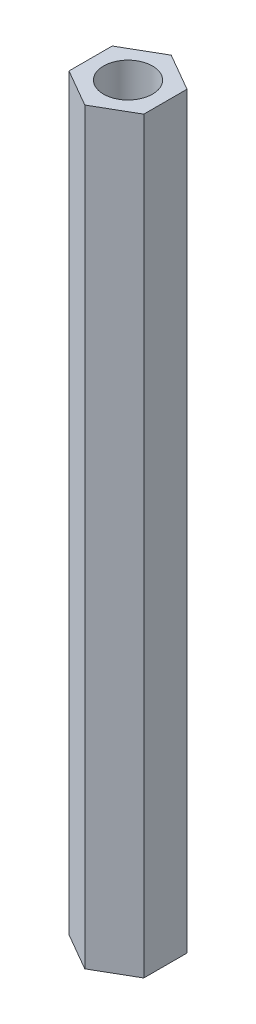
SolidWorks part; units mm, degrees
ref_plane "Front Plane" through (0, 0, 0) normal (0, 0, 1) x (1, 0, 0)
ref_plane "Top Plane" through (0, 0, 0) normal (0, 1, 0) x (1, 0, 0)
ref_plane "Right Plane" through (0, 0, 0) normal (1, 0, 0) x (0, 0, -1)
sketch "Sketch1" plane through (0, 0, 0) normal (0, 1, 0) x (1, 0, 0)
  line L0 (2.5002, 1.4435) -> (2.5002, -1.4435)
  line L1 (2.5002, -1.4435) -> (0, -2.887)
  line L2 (0, -2.887) -> (-2.5002, -1.4435)
  line L3 (-2.5002, -1.4435) -> (-2.5002, 1.4435)
  line L4 (-2.5002, 1.4435) -> (0, 2.887)
  line L5 (0, 2.887) -> (2.5002, 1.4435)
  circle A0 centre (0, 0) radius 1.635
  dimension "D1" = 3.27
  dimension "D3" = 2.887
  dimension "D4" = 2.887
  dimension "D5" = 2.887
  dimension "D6" = 2.887
  dimension "D7" = 2.887
extrude "Boss-Extrude1" add sketch "Sketch1" along normal blind 50
